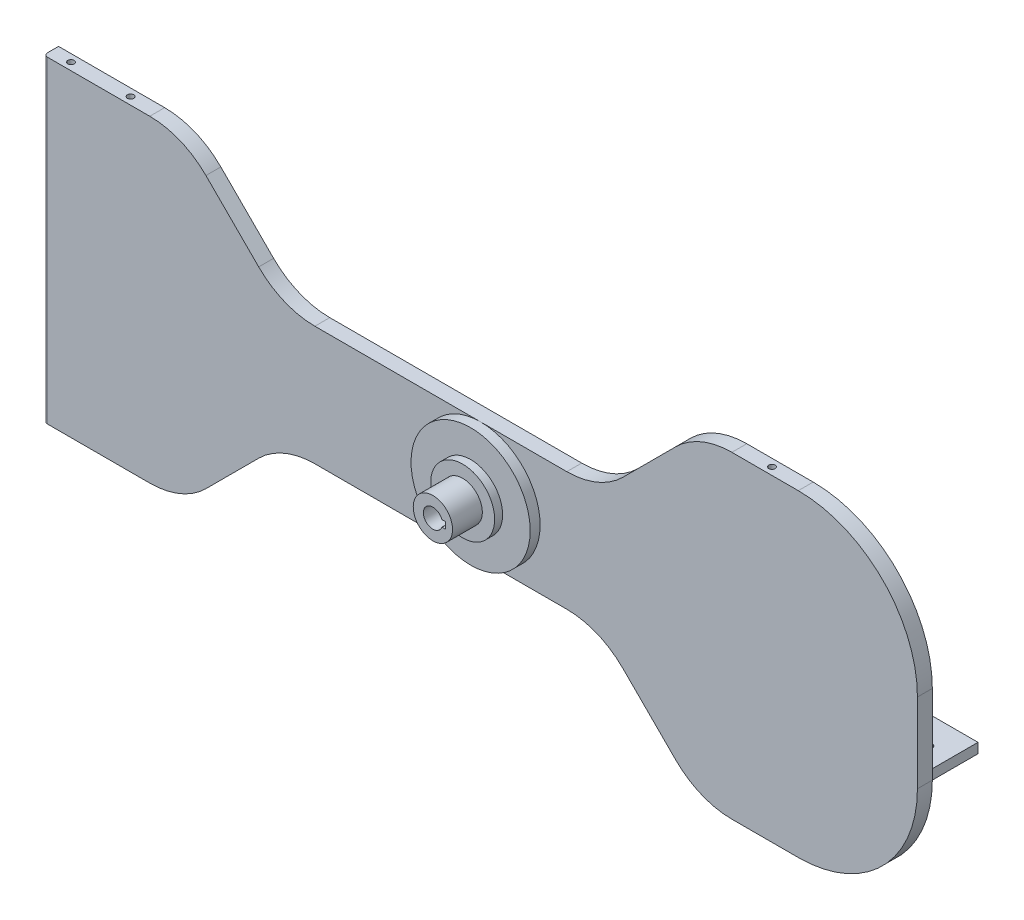
SolidWorks part; units mm, degrees
material "ABS"
ref_plane "Front Plane" through (0, 0, 0) normal (0, 0, 1) x (1, 0, 0)
ref_plane "Top Plane" through (0, 0, 0) normal (0, 1, 0) x (1, 0, 0)
ref_plane "Right Plane" through (0, 0, 0) normal (1, 0, 0) x (0, 0, -1)
sketch "Sketch1" plane through (0, 0, 0) normal (0, 0, 1) x (1, 0, 0)
  line L0 (103.779, 188.321) -> (137.521, 154.579)
  line L1 (0, 0) -> (67.858, 0)
  line L2 (0, 0) -> (0, 203.2)
  line L3 (0, 203.2) -> (67.858, 203.2)
  line L4 (558.8, 76.2) -> (558.8, 127)
  line L5 (173.442, 139.7) -> (334.558, 139.7)
  line L6 (370.479, 154.579) -> (404.221, 188.321)
  line L7 (137.521, 48.621) -> (103.779, 14.879)
  line L8 (173.442, 63.5) -> (334.558, 63.5)
  line L9 (370.479, 48.621) -> (404.221, 14.879)
  line L10 (440.142, 0) -> (482.6, 0)
  line L11 (440.142, 203.2) -> (482.6, 203.2)
  line L12 (-122.1327, 101.6) -> (644.6154, 101.6) construction
  arc A0 (137.521, 154.579) -> (173.442, 139.7) centre (173.442, 190.5) ccw
  arc A1 (67.858, 203.2) -> (103.779, 188.321) centre (67.858, 152.4) cw
  arc A2 (334.558, 139.7) -> (370.479, 154.579) centre (334.558, 190.5) ccw
  arc A3 (404.221, 188.321) -> (440.142, 203.2) centre (440.142, 152.4) cw
  arc A4 (334.558, 63.5) -> (370.479, 48.621) centre (334.558, 12.7) cw
  arc A5 (137.521, 48.621) -> (173.442, 63.5) centre (173.442, 12.7) cw
  arc A6 (67.858, 0) -> (103.779, 14.879) centre (67.858, 50.8) ccw
  arc A7 (440.142, 0) -> (404.221, 14.879) centre (440.142, 50.8) cw
  arc A8 (482.6, 203.2) -> (558.8, 127) centre (482.6, 127) cw
  arc A9 (482.6, 0) -> (558.8, 76.2) centre (482.6, 76.2) ccw
  point P17 (152.4, 139.7)
  point P22 (355.6, 139.7)
  point P25 (419.1, 203.2)
  point P28 (355.6, 63.5)
  point P31 (152.4, 63.5)
  dimension "D14" = 50.8
  dimension "D15" = 50.8
  dimension "D16" = 50.8
  dimension "D17" = 50.8
  dimension "D18" = 50.8
  dimension "D19" = 50.8
  dimension "D20" = 50.8
  dimension "D21" = 50.8
  dimension "D22" = 76.2
  dimension "D23" = 76.2
  dimension "D1" = 558.8
  dimension "D2" = 203.2
  dimension "D3" = 152.4
  dimension "D4" = 152.4
  dimension "D5" = 135
  dimension "D6" = 135
  dimension "D7" = 135
  dimension "D8" = 135
  dimension "D9" = 203.2
  dimension "D10" = 203.2
  dimension "D11" = 101.6
  dimension "D12" = 38.1
  dimension "D13" = 38.1
extrude "Boss-Extrude1" add sketch "Sketch1" along normal blind 9.525
sketch "Sketch6" plane through (0, 0, 0) normal (0, 0, -1) x (-1, 0, 0)
  line L0 (-582.6653, 101.6) -> (106.9124, 101.6) construction
  line L1 (-67.858, 203.2) -> (0, 203.2) construction
  line L2 (0, 203.2) -> (0, 0) construction
  line L3 (-552.45, 76.2) -> (-43.18, 76.2)
  line L4 (-552.45, 76.2) -> (-552.45, 69.85)
  line L5 (-552.45, 69.85) -> (-43.18, 69.85)
  line L6 (-43.18, 76.2) -> (-43.18, 69.85)
  line L7 (-558.8, 76.2) -> (-558.8, 127) construction
  dimension "D1" = 101.6
  dimension "D2" = 25.4
  dimension "D3" = 6.35
  dimension "D4" = 43.18
  dimension "D5" = 6.35
extrude "Boss-Extrude3" add sketch "Sketch6" along normal blind 35.56
sketch "Sketch7" plane through (0, 76.2, 0) normal (0, 1, 0) x (1, 0, 0)
  line L0 (26.1348, 17.78) -> (601.3939, 17.78) construction
  line L1 (43.18, 35.56) -> (552.45, 35.56) construction
  line L2 (43.18, 35.56) -> (43.18, 0) construction
  line L3 (552.45, 35.56) -> (552.45, 0) construction
  circle A0 centre (58.166, 17.78) radius 2.286
  circle A1 centre (538.734, 17.78) radius 2.286
  dimension "D3" = 4.572
  dimension "D5" = 4.572
  dimension "D1" = 17.78
  dimension "D2" = 14.986
  dimension "D4" = 13.716
extrude "Cut-Extrude4" cut sketch "Sketch7" against normal through all
hole_wizard "#10-32 Tapped Hole1" positions "Sketch9" profile "Sketch8" tap size "#10-32" standard "Ansi Inch"
sketch "Sketch9" plane through (0, 203.2, 0) normal (0, 1, 0) x (-1, 0, 0)
  line L0 (-67.858, 0) -> (0, 0) construction
  line L1 (0, 9.525) -> (0, 0) construction
  line L2 (-482.6, 0) -> (-440.142, 0) construction
  line L3 (-482.6, 9.525) -> (-482.6, 0) construction
  point P0 (-12.7, 4.7625)
  point P1 (-50.8, 4.7625)
  point P3 (-461.01, 4.7625)
  dimension "D1" = 4.7625
  dimension "D2" = 4.7625
  dimension "D3" = 12.7
  dimension "D4" = 38.1
  dimension "D5" = 4.7625
  dimension "D6" = 21.59
sketch "Sketch8" plane through (12.7, 203.2, 4.7625) normal (1, 0, 0) x (0, 0, 1)
  line L0 (0, 0) -> (0, 14.9293)
  line L1 (0, 14.9293) -> (2.0193, 13.716)
  line L2 (2.0193, 13.716) -> (2.0193, 0)
  line L5 (2.0193, 0) -> (0, 0)
  line L10 (0, 14.9293) -> (-2.0193, 13.716) construction
  line L11 (0, -6.35) -> (0, 107.95) construction
  dimension "Tap Drill Dia." = 4.0386
  dimension "Tap Drill Depth" = 13.716
  dimension "Drill Angle" = 118
cosmetic thread "Hole Thread1" parameters "D1"=9.652, "D2"=4.826
cosmetic thread "Hole Thread2" parameters "D1"=9.652, "D2"=4.826
cosmetic thread "Hole Thread3" parameters "D1"=9.652, "D2"=4.826
hole_wizard "#10-32 Tapped Hole2" positions "Sketch11" profile "Sketch10" tap size "#10-32" standard "Ansi Inch"
sketch "Sketch11" plane through (0, 0, 0) normal (0, -1, 0) x (1, 0, 0)
  line L0 (0, 9.525) -> (67.858, 9.525) construction
  line L1 (0, 9.525) -> (0, 0) construction
  line L2 (440.142, 9.525) -> (482.6, 9.525) construction
  line L3 (482.6, 9.525) -> (482.6, 0) construction
  point P0 (12.7, 4.7625)
  point P1 (50.8, 4.7625)
  point P3 (461.01, 4.7625)
  point P12 (482.6, 4.7625)
  dimension "D1" = 4.7625
  dimension "D2" = 38.1
  dimension "D3" = 4.7625
  dimension "D4" = 12.7
  dimension "D5" = 4.7625
  dimension "D6" = 21.59
sketch "Sketch10" plane through (12.7, 0, 4.7625) normal (1, 0, 0) x (0, 0, -1)
  line L0 (0, 0) -> (0, 14.9293)
  line L1 (0, 14.9293) -> (2.0193, 13.716)
  line L2 (2.0193, 13.716) -> (2.0193, 0)
  line L5 (2.0193, 0) -> (0, 0)
  line L10 (0, 14.9293) -> (-2.0193, 13.716) construction
  line L11 (0, -6.35) -> (0, 107.95) construction
  dimension "Tap Drill Dia." = 4.0386
  dimension "Tap Drill Depth" = 13.716
  dimension "Drill Angle" = 118
cosmetic thread "Hole Thread4" parameters "D1"=9.652, "D2"=4.826
cosmetic thread "Hole Thread5" parameters "D1"=9.652, "D2"=4.826
cosmetic thread "Hole Thread6" parameters "D1"=9.652, "D2"=4.826
sketch "Sketch12" plane through (0, 0, 9.525) normal (0, 0, 1) x (1, 0, 0)
  line L0 (0, 203.2) -> (0, 0) construction
  line L2 (0, 0) -> (67.858, 0) construction
  circle A0 centre (279.4, 101.6) radius 38.1
  dimension "D3" = 76.2
  dimension "D1" = 279.4
  dimension "D2" = 101.6
extrude "Boss-Extrude4" add sketch "Sketch12" along normal blind 6.35
sketch "Sketch13" plane through (0, 0, 15.875) normal (0, 0, 1) x (1, 0, 0)
  circle A0 centre (279.4, 101.6) radius 20.447
  dimension "D1" = 40.894
extrude "Boss-Extrude5" add sketch "Sketch13" along normal blind 5.08
sketch "Sketch14" plane through (0, 0, 20.955) normal (0, 0, 1) x (1, 0, 0)
  circle A0 centre (279.4, 101.6) radius 12.573
  dimension "D1" = 25.146
extrude "Boss-Extrude6" add sketch "Sketch14" along normal blind 19.05
sketch "Sketch15" plane through (0, 0, 40.005) normal (0, 0, 1) x (1, 0, 0)
  line L0 (287.401, 103.7082) -> (287.401, 99.4918)
  line L1 (285.2943, 103.7082) -> (287.401, 103.7082)
  line L2 (285.2943, 99.4918) -> (287.401, 99.4918)
  arc A0 (285.0585, 103.8677) -> (285.0585, 99.3323) centre (279.4, 101.6) ccw
  arc A1 (285.0585, 103.8677) -> (285.2943, 103.7082) centre (285.2943, 103.9622) ccw
  arc A2 (285.0585, 99.3323) -> (285.2943, 99.4918) centre (285.2943, 99.2378) cw
  dimension "D1" = 12.192
  dimension "D5" = 0.254
  dimension "D6" = 0.254
  dimension "D2" = 8.001
  dimension "D3" = 2.1082
  dimension "D4" = 2.1082
extrude "Cut-Extrude5" cut sketch "Sketch15" against normal blind 19.05
fillet "Fillet1" radius 2.54 1 edges at (0, 101.6, 9.525)
hole_wizard "#10-32 Tapped Hole3" positions "3DSketch1" profile "Sketch16" tap size "#10-32" standard "Ansi Inch" end condition through all
sketch3d "3DSketch1"
  line L0 (273.304, 101.6, 20.955) -> (287.401, 101.6, 20.955) construction
  line L1 (287.401, 99.4918, 20.955) -> (287.401, 103.7082, 20.955) construction
  line L2 (279.4, 101.6, 20.955) -> (279.4, 107.696, 20.955) construction
  line L3 (279.4, 101.6, 40.005) -> (279.4, 101.6, 20.955) construction
  line L4 (279.4, 101.6, 20.955) -> (279.4, 101.6, 15.875) construction
  line L5 (279.4, 101.6, 20.955) -> (279.4, 95.504, 20.955) construction
  arc A0 (285.0585, 103.8677, 20.955) -> (285.0585, 99.3323, 20.955) centre (279.4, 101.6, 20.955) ccw construction
  point P0 (279.4, 101.6, 20.955)
  point P8 (279.4, 101.6, 27.051)
sketch "Sketch16" plane through (279.4, 101.6, 20.955) normal (1, 0, 0) x (0, -1, 0)
  line L0 (0, 0) -> (0, 56.515)
  line L1 (0, 56.515) -> (2.0193, 56.515)
  line L2 (2.0193, 56.515) -> (2.0193, 0)
  line L5 (2.0193, 0) -> (0, 0)
  line L11 (0, -6.35) -> (0, 107.95) construction
  dimension "Thru Tap Drill Dia." = 4.0386
  dimension "Thru Tap Drill Depth" = 56.515
cosmetic thread "Hole Thread7" parameters "D2"=4.826
